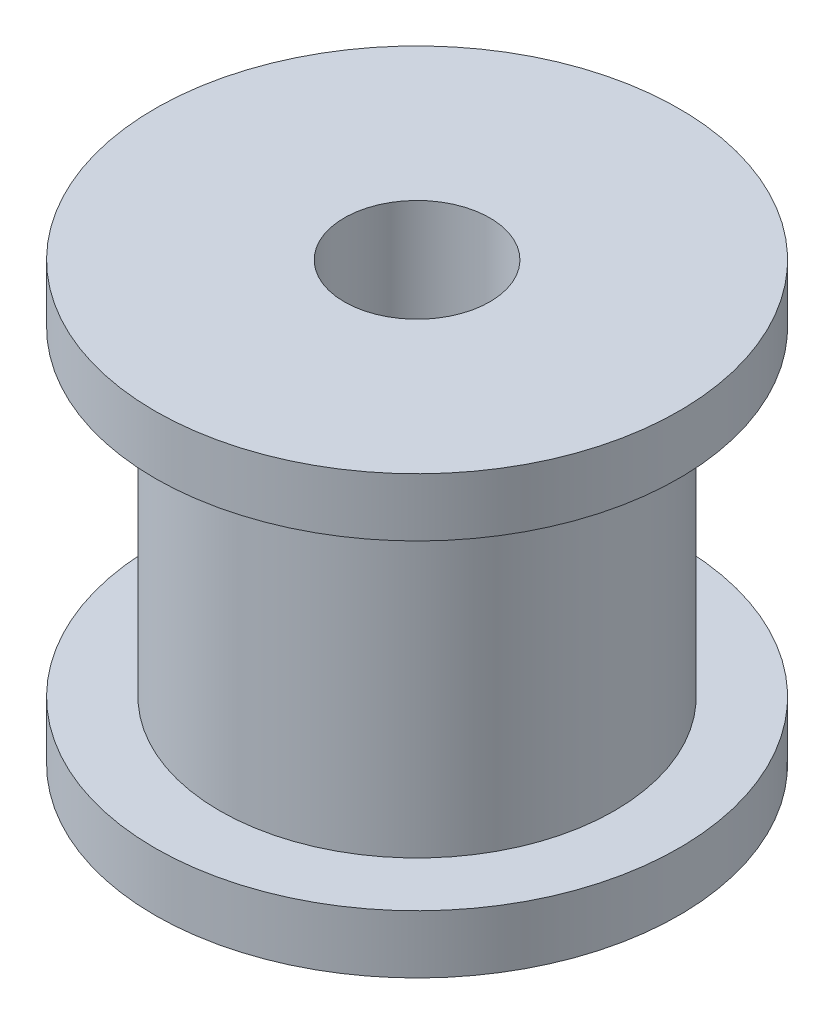
SolidWorks part; units mm, degrees
material "AISI 304"
ref_plane "前视基准面" through (0, 0, 0) normal (0, 0, 1) x (1, 0, 0)
ref_plane "上视基准面" through (0, 0, 0) normal (0, 1, 0) x (1, 0, 0)
ref_plane "右视基准面" through (0, 0, 0) normal (1, 0, 0) x (0, 0, -1)
other "Configuration Table"
sketch "草图1" plane through (0, 0, 0) normal (0, 1, 0) x (1, 0, 0)
  circle A0 centre (0, 0) radius 9
  dimension "D1" = 18
extrude "凸台-拉伸1" add sketch "草图1" along normal blind 2
sketch "草图2" plane through (0, 2, 0) normal (0, 1, 0) x (1, 0, 0)
  circle A0 centre (0, 0) radius 6.78
  dimension "D1" = 13.56
extrude "凸台-拉伸2" add sketch "草图2" along normal blind 11
sketch "草图3" plane through (0, 13, 0) normal (0, 1, 0) x (1, 0, 0)
  circle A0 centre (0, 0) radius 9
  dimension "D1" = 18
extrude "凸台-拉伸3" add sketch "草图3" along normal blind 2
sketch "草图4" plane through (0, 15, 0) normal (0, 1, 0) x (1, 0, 0)
  circle A0 centre (0, 0) radius 2.5
  dimension "D1" = 5
extrude "切除-拉伸1" cut sketch "草图4" against normal blind 26
